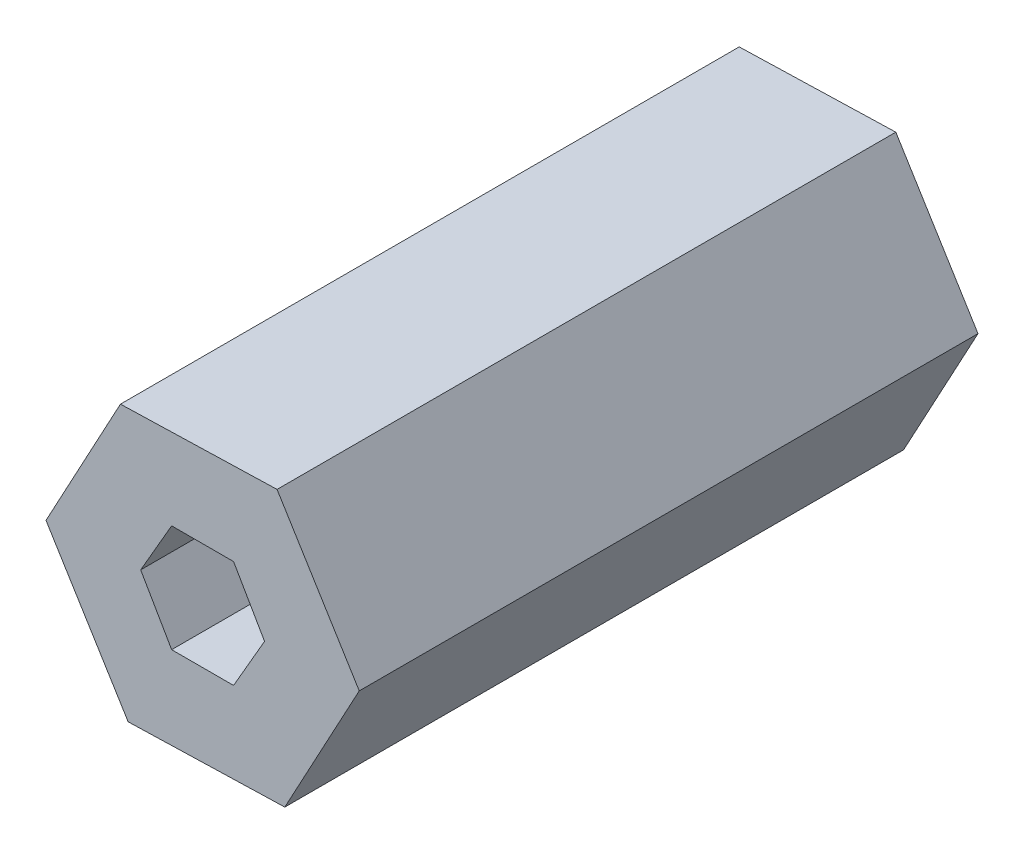
SolidWorks part; units mm, degrees
ref_plane "Front Plane" through (0, 0, 0) normal (0, 0, 1) x (1, 0, 0)
ref_plane "Top Plane" through (0, 0, 0) normal (0, 1, 0) x (1, 0, 0)
ref_plane "Right Plane" through (0, 0, 0) normal (1, 0, 0) x (0, 0, -1)
sketch "Sketch3" plane through (0, 0, 0) normal (0, 0, 1) x (1, 0, 0)
  line L1 (2.8983, 0) -> (1.4491, 2.51)
  line L2 (1.4491, 2.51) -> (-1.4491, 2.51)
  line L3 (-1.4491, 2.51) -> (-2.8983, 0)
  line L4 (-2.8983, 0) -> (-1.4491, -2.51)
  line L5 (-1.4491, -2.51) -> (1.4491, -2.51)
  line L6 (1.4491, -2.51) -> (2.8983, 0)
  line L7 (4.613, 0) -> (2.3065, 3.995)
  line L8 (2.3065, 3.995) -> (-2.3065, 3.995)
  line L9 (-2.3065, 3.995) -> (-4.613, 0)
  line L10 (-4.613, 0) -> (-2.3065, -3.995)
  line L11 (-2.3065, -3.995) -> (2.3065, -3.995)
  line L12 (2.3065, -3.995) -> (4.613, 0)
  line L13 (7.3294, 0.2091) -> (3.4836, 6.452)
  line L14 (3.4836, 6.452) -> (-3.8458, 6.2428)
  line L15 (-3.8458, 6.2428) -> (-7.3294, -0.2091)
  line L16 (-7.3294, -0.2091) -> (-3.4836, -6.452)
  line L17 (-3.4836, -6.452) -> (3.8458, -6.2428)
  line L18 (3.8458, -6.2428) -> (7.3294, 0.2091)
  circle A0 centre (0, 0) radius 2.51 construction
  circle A1 centre (0, 0) radius 3.995 construction
  circle A2 centre (0, 0) radius 6.35 construction
sketch "Sketch4" plane through (0, 0, 0) normal (0, 0, 1) x (1, 0, 0)
  line L1 (2.8983, 0) -> (1.4491, 2.51)
  line L2 (1.4491, 2.51) -> (-1.4491, 2.51)
  line L3 (-1.4491, 2.51) -> (-2.8983, 0)
  line L4 (-2.8983, 0) -> (-1.4491, -2.51)
  line L5 (-1.4491, -2.51) -> (1.4491, -2.51)
  line L6 (1.4491, -2.51) -> (2.8983, 0)
  line L7 (4.613, 0) -> (2.3065, 3.995)
  line L8 (2.3065, 3.995) -> (-2.3065, 3.995)
  line L9 (-2.3065, 3.995) -> (-4.613, 0)
  line L10 (-4.613, 0) -> (-2.3065, -3.995)
  line L11 (-2.3065, -3.995) -> (2.3065, -3.995)
  line L12 (2.3065, -3.995) -> (4.613, 0)
  line L13 (7.3294, 0.2091) -> (3.4836, 6.452)
  line L14 (3.4836, 6.452) -> (-3.8458, 6.2428)
  line L15 (-3.8458, 6.2428) -> (-7.3294, -0.2091)
  line L16 (-7.3294, -0.2091) -> (-3.4836, -6.452)
  line L17 (-3.4836, -6.452) -> (3.8458, -6.2428)
  line L18 (3.8458, -6.2428) -> (7.3294, 0.2091)
  circle A0 centre (0, 0) radius 2.51 construction
  circle A1 centre (0, 0) radius 3.995 construction
  circle A2 centre (0, 0) radius 6.35 construction
extrude "Boss-Extrude2" add sketch "Sketch4" along normal blind 28.956 contours L17 L18 L13 L14 L15 L16 L12 L11 L10 L9 L8 L7 | L11 L12 L7 L8 L9 L10 L6 L5 L4 L3 L2 L1
